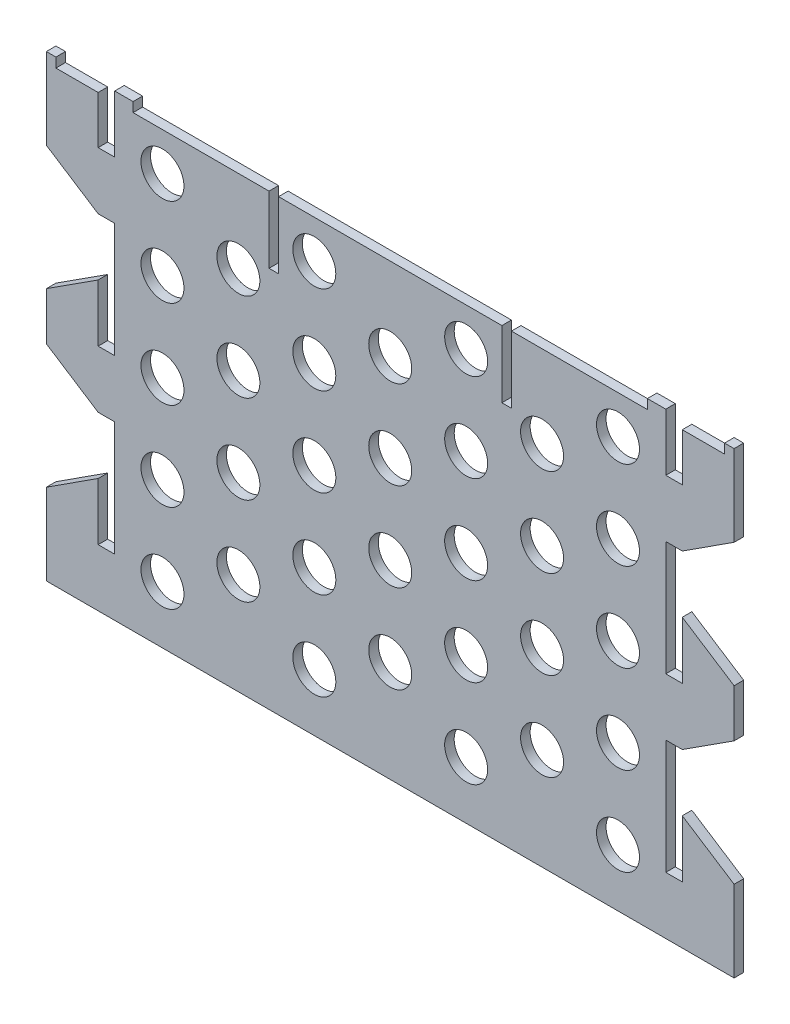
SolidWorks part; units mm, degrees
material "Plywood"
ref_plane "Front Plane" through (0, 0, 0) normal (0, 0, 1) x (1, 0, 0)
ref_plane "Top Plane" through (0, 0, 0) normal (0, 1, 0) x (1, 0, 0)
ref_plane "Right Plane" through (0, 0, 0) normal (1, 0, 0) x (0, 0, -1)
sketch "Sketch1" plane through (0, 0, 0) normal (0, 1, 0) x (1, 0, 0)
  line L0 (-381, -659.9114) -> (381, -659.9114) construction
  line L1 (-381, -659.9114) -> (381, -659.9114)
  line L2 (-381, -647.2114) -> (381, -647.2114)
  line L3 (-381, -647.2114) -> (-381, -659.9114)
  line L4 (381, -647.2114) -> (381, -659.9114)
  dimension "D1" = 12.7
extrude "Boss-Extrude1" add sketch "Sketch1" along normal blind 609.6
sketch "Sketch2" plane through (381, 0, 0) normal (1, 0, 0) x (0, 0, -1)
  line L4 (-659.9114, 0) -> (-647.2114, 0)
  line L5 (-647.2114, 0) -> (-647.2114, 609.6)
  line L6 (-647.2114, 609.6) -> (-659.9114, 609.6)
  line L7 (-659.9114, 609.6) -> (-659.9114, 0)
  line L8 (-659.9114, 0) -> (-647.2114, 0)
  line L9 (-647.2114, 0) -> (-647.2114, 609.6)
  line L10 (-647.2114, 609.6) -> (-659.9114, 609.6)
  line L11 (-659.9114, 609.6) -> (-659.9114, 0)
  dimension "D1" = 0
extrude "Boss-Extrude2" add sketch "Sketch2" along normal blind 76.2
mirror "Mirror1" about plane through (0, 0, 0) normal (1, 0, 0) of "Boss-Extrude2"
sketch "Sketch3" plane through (0, 0, 659.9114) normal (0, 0, 1) x (1, 0, 0)
  line L3 (-457.2, 0) -> (457.2, 0) construction
  line L5 (-457.2, 609.6) -> (457.2, 609.6) construction
  line L6 (-457.2, 76.2) -> (457.2, 76.2) construction
  line L8 (-388.3323, 0) -> (-388.3323, 609.6) construction
  line L9 (-366.3353, 0) -> (-366.3353, 609.6) construction
  line L10 (366.3353, 0) -> (366.3353, 609.6) construction
  line L11 (-457.2, 457.2) -> (457.2, 457.2) construction
  line L12 (-457.2, 533.4) -> (457.2, 533.4) construction
  line L26 (388.3323, 0) -> (388.3323, 609.6) construction
  line L44 (-457.2, 152.4) -> (457.2, 152.4) construction
  line L65 (-457.2, 0) -> (457.2, 0) construction
  line L67 (-457.2, 609.6) -> (457.2, 609.6) construction
  line L68 (-457.2, 76.2) -> (457.2, 76.2) construction
  line L69 (-457.2, 609.6) -> (457.2, 609.6) construction
  line L70 (-388.3323, 0) -> (-388.3323, 609.6) construction
  line L71 (-366.3353, 0) -> (-366.3353, 609.6) construction
  line L72 (366.3353, 0) -> (366.3353, 609.6) construction
  line L73 (388.3323, 0) -> (388.3323, 609.6) construction
  line L93 (-457.2, 152.4) -> (457.2, 152.4) construction
  line L94 (-457.2, 304.8) -> (457.2, 304.8) construction
  line L95 (-457.2, 609.6) -> (-457.2, 0) construction
  line L113 (457.2, 609.6) -> (457.2, 0) construction
  line L114 (-457.2, 228.6) -> (457.2, 228.6) construction
  line L115 (-457.2, 381) -> (457.2, 381) construction
  line L116 (0, 609.6) -> (0, 0) construction
  line L117 (366.3353, 609.6) -> (-366.3353, 609.6)
  line L118 (-366.3353, 609.6) -> (-366.3353, 533.4)
  line L119 (-366.3353, 533.4) -> (-388.3323, 533.4)
  line L120 (-388.3323, 533.4) -> (-388.3323, 609.6)
  line L121 (-388.3323, 609.6) -> (-457.2, 609.6)
  line L122 (-457.2, 609.6) -> (-457.2, 457.2)
  line L123 (-457.2, 457.2) -> (-366.3353, 457.2)
  line L124 (-366.3353, 457.2) -> (-366.3353, 304.8)
  line L125 (-366.3353, 304.8) -> (-388.3323, 304.8)
  line L126 (-388.3323, 304.8) -> (-388.3323, 381)
  line L127 (-388.3323, 381) -> (-457.2, 381)
  line L128 (-457.2, 381) -> (-457.2, 228.6)
  line L129 (-457.2, 228.6) -> (-366.3353, 228.6)
  line L130 (-366.3353, 228.6) -> (-366.3353, 76.2)
  line L131 (-366.3353, 76.2) -> (-388.3323, 76.2)
  line L132 (-388.3323, 76.2) -> (-388.3323, 152.4)
  line L133 (-388.3323, 152.4) -> (-457.2, 152.4)
  line L134 (-457.2, 152.4) -> (-457.2, 0)
  line L135 (-457.2, 0) -> (457.2, 0)
  line L136 (366.3353, 0) -> (366.3353, 609.6) construction
  line L137 (388.3323, 0) -> (388.3323, 609.6) construction
  line L138 (457.2, 152.4) -> (457.2, 0)
  line L139 (388.3323, 152.4) -> (457.2, 152.4)
  line L140 (388.3323, 76.2) -> (388.3323, 152.4)
  line L141 (366.3353, 76.2) -> (388.3323, 76.2)
  line L142 (366.3353, 228.6) -> (366.3353, 76.2)
  line L143 (457.2, 228.6) -> (366.3353, 228.6)
  line L144 (457.2, 381) -> (457.2, 228.6)
  line L145 (388.3323, 381) -> (457.2, 381)
  line L146 (388.3323, 304.8) -> (388.3323, 381)
  line L147 (366.3353, 304.8) -> (388.3323, 304.8)
  line L148 (366.3353, 457.2) -> (366.3353, 304.8)
  line L149 (457.2, 457.2) -> (366.3353, 457.2)
  line L150 (457.2, 609.6) -> (457.2, 457.2)
  line L151 (388.3323, 609.6) -> (457.2, 609.6)
  line L152 (388.3323, 533.4) -> (388.3323, 609.6)
  line L153 (366.3353, 533.4) -> (388.3323, 533.4)
  line L154 (366.3353, 609.6) -> (366.3353, 533.4)
  point P0 (-457.2, 457.2)
  point P61 (-366.3353, 548.966)
  point P63 (-366.3353, 484.904)
  point P64 (0, 0)
  point P65 (0, 0)
  dimension "D1" = 76.2
  dimension "D2" = 76.2
  dimension "D3" = 76.2
  dimension "D4" = 76.2
extrude "Cut-Extrude1" cut sketch "Sketch3" against normal up to vertex (12.7 mm away) flip side to cut
sketch "Sketch4" plane through (0, 0, 659.9114) normal (0, 0, 1) x (1, 0, 0)
  line L0 (0, 0) -> (0, 609.6)
  line L1 (-366.3353, 609.6) -> (366.3353, 609.6) construction
sketch "Sketch6" plane through (0, 609.6, 0) normal (0, 1, 0) x (1, 0, 0)
  line L20 (-444.5, -647.2114) -> (-444.5, -659.9114)
  line L21 (-444.5, -659.9114) -> (-388.3323, -659.9114)
  line L22 (-388.3323, -659.9114) -> (-388.3323, -647.2114)
  line L23 (-388.3323, -647.2114) -> (-444.5, -647.2114)
  line L24 (-444.5, -647.2114) -> (-444.5, -659.9114)
  line L25 (-444.5, -659.9114) -> (-388.3323, -659.9114)
  line L26 (-388.3323, -659.9114) -> (-388.3323, -647.2114)
  line L27 (-388.3323, -647.2114) -> (-444.5, -647.2114)
  line L28 (341.9177, -659.9114) -> (341.9177, -647.2114)
  line L29 (-341.9177, -659.9114) -> (341.9177, -659.9114)
  line L30 (-341.9177, -647.2114) -> (-341.9177, -659.9114)
  line L31 (341.9177, -647.2114) -> (-341.9177, -647.2114)
  line L32 (341.9177, -659.9114) -> (341.9177, -647.2114)
  line L33 (-341.9177, -659.9114) -> (341.9177, -659.9114)
  line L34 (-341.9177, -647.2114) -> (-341.9177, -659.9114)
  line L35 (341.9177, -647.2114) -> (-341.9177, -647.2114)
  line L36 (388.3323, -647.2114) -> (388.3323, -659.9114)
  line L37 (444.5, -647.2114) -> (388.3323, -647.2114)
  line L38 (444.5, -659.9114) -> (444.5, -647.2114)
  line L39 (388.3323, -659.9114) -> (444.5, -659.9114)
  line L48 (388.3323, -647.2114) -> (388.3323, -659.9114)
  line L49 (444.5, -647.2114) -> (388.3323, -647.2114)
  line L50 (444.5, -659.9114) -> (444.5, -647.2114)
  line L51 (388.3323, -659.9114) -> (444.5, -659.9114)
  dimension "D1" = 0
  dimension "D2" = 0
  dimension "D3" = 0
extrude "Cut-Extrude2" cut sketch "Sketch6" against normal up to vertex (12.7 mm away)
sketch "Sketch14" plane through (0, 0, 659.9114) normal (0, 0, 1) x (1, 0, 0)
  line L0 (-388.3323, 457.2) -> (-457.2, 501.65)
  line L1 (-457.2, 609.6) -> (-457.2, 457.2) construction
  line L3 (-457.2, 457.2) -> (-388.3323, 457.2)
  line L4 (0, 0) -> (0, 596.9) construction
  line L5 (-457.2, 0) -> (457.2, 0) construction
  line L6 (-341.9177, 596.9) -> (341.9177, 596.9) construction
  line L7 (-388.3323, 381) -> (-457.2, 336.55)
  line L8 (-457.2, 381) -> (-457.2, 228.6) construction
  line L12 (-457.2, 336.55) -> (-457.2, 381)
  line L13 (-457.2, 381) -> (-388.3323, 381)
  line L14 (-388.3323, 152.4) -> (-457.2, 107.95)
  line L15 (-457.2, 152.4) -> (-457.2, 0) construction
  line L16 (-457.2, 107.95) -> (-457.2, 152.4)
  line L17 (-457.2, 152.4) -> (-388.3323, 152.4)
  line L18 (457.2, 152.4) -> (388.3323, 152.4)
  line L19 (457.2, 107.95) -> (457.2, 152.4)
  line L20 (388.3323, 152.4) -> (457.2, 107.95)
  line L21 (457.2, 381) -> (388.3323, 381)
  line L22 (457.2, 336.55) -> (457.2, 381)
  line L23 (388.3323, 381) -> (457.2, 336.55)
  line L24 (457.2, 457.2) -> (388.3323, 457.2)
  line L25 (457.2, 501.65) -> (457.2, 457.2)
  line L26 (388.3323, 457.2) -> (457.2, 501.65)
  line L33 (-457.2, 273.05) -> (-388.3323, 228.6)
  line L34 (-457.2, 228.6) -> (-366.3353, 228.6) construction
  line L35 (-388.3323, 228.6) -> (-457.2, 228.6)
  line L36 (-457.2, 228.6) -> (-457.2, 273.05)
  line L37 (-457.2, 501.65) -> (-457.2, 457.2)
  line L38 (388.3323, 228.6) -> (457.2, 228.6)
  line L39 (457.2, 273.05) -> (388.3323, 228.6)
  line L40 (457.2, 228.6) -> (457.2, 273.05)
  line L41 (-457.2, 457.2) -> (-366.3353, 457.2) construction
  dimension "D1" = 44.45
extrude "Cut-Extrude5" cut sketch "Sketch14" against normal up to vertex (12.7 mm away)
ref_plane "Plane1" through (0, 304.8, 0) normal (0, -1, 0) x (-1, 0, 0)
sketch "Sketch7" plane through (0, 0, 659.9114) normal (0, 0, 1) x (1, 0, 0)
  line L1171 (148.4706, 508) -> (161.1706, 508)
  line L1172 (161.1706, 508) -> (161.1706, 596.9)
  line L1173 (161.1706, 596.9) -> (148.4706, 596.9)
  line L1174 (148.4706, 596.9) -> (148.4706, 508)
  line L1175 (148.4706, 508) -> (161.1706, 508)
  line L1176 (161.1706, 508) -> (161.1706, 596.9)
  line L1177 (161.1706, 596.9) -> (148.4706, 596.9)
  line L1178 (148.4706, 596.9) -> (148.4706, 508)
  line L1179 (-148.4706, 596.9) -> (-161.1706, 596.9)
  line L1180 (-148.4706, 508) -> (-148.4706, 596.9)
  line L1181 (-161.1706, 508) -> (-148.4706, 508)
  line L1182 (-161.1706, 596.9) -> (-161.1706, 508)
  line L1183 (-148.4706, 596.9) -> (-161.1706, 596.9)
  line L1184 (-148.4706, 508) -> (-148.4706, 596.9)
  line L1185 (-161.1706, 508) -> (-148.4706, 508)
  line L1186 (-161.1706, 596.9) -> (-161.1706, 508)
  dimension "D1" = 0
  dimension "D2" = 0
extrude "Cut-Extrude3" cut sketch "Sketch7" against normal up to vertex (12.7 mm away)
mirror "Mirror2" about plane through (0, 304.8, 0) normal (0, -1, 0) of "Cut-Extrude3", "Cut-Extrude2"
sketch "Sketch8" [suppressed] plane through (0, 609.6, 0) normal (0, 1, 0) x (1, 0, 0)
  line L16 (366.3353, -647.2114) -> (366.3353, -659.9114) construction
  line L17 (-366.3353, -647.2114) -> (-366.3353, -659.9114) construction
  line L18 (366.3353, -647.2114) -> (366.3353, -659.9114)
  line L19 (-366.3353, -647.2114) -> (-366.3353, -659.9114)
  line L20 (-366.3353, -647.2114) -> (366.3353, -647.2114)
  line L21 (366.3353, -659.9114) -> (-366.3353, -659.9114)
extrude "Boss-Extrude3" [suppressed] add sketch "Sketch8" against normal up to vertex
sketch "Sketch9" [suppressed] plane through (0, 609.6, 0) normal (0, 1, 0) x (1, 0, 0)
  line L0 (388.3323, -647.2114) -> (388.3323, -659.9114) construction
  line L1 (457.2, -647.2114) -> (457.2, -659.9114) construction
  line L2 (-457.2, -647.2114) -> (-457.2, -659.9114) construction
  line L3 (-388.3323, -659.9114) -> (-388.3323, -647.2114) construction
  line L4 (388.3323, -647.2114) -> (388.3323, -659.9114)
  line L5 (457.2, -647.2114) -> (457.2, -659.9114)
  line L6 (-457.2, -647.2114) -> (-457.2, -659.9114)
  line L7 (-388.3323, -659.9114) -> (-388.3323, -647.2114)
  line L8 (-457.2, -659.9114) -> (-388.3323, -659.9114)
  line L9 (-388.3323, -647.2114) -> (-457.2, -647.2114)
  line L10 (388.3323, -659.9114) -> (457.2, -659.9114)
  line L11 (457.2, -647.2114) -> (388.3323, -647.2114)
extrude "Boss-Extrude4" [suppressed] add sketch "Sketch9" against normal up to vertex
sketch "Sketch10" plane through (0, 0, 659.9114) normal (0, 0, 1) x (1, 0, 0)
  line L0 (-148.4706, 12.7) -> (148.4706, 12.7) construction
  line L1 (-366.3353, 609.6) -> (366.3353, 609.6) construction
  line L2 (-366.3353, 609.6) -> (-366.3353, 12.7) construction
  line L3 (-366.3353, 12.7) -> (366.3353, 12.7) construction
  line L4 (366.3353, 609.6) -> (366.3353, 12.7) construction
  line L5 (-366.3353, 311.15) -> (366.3353, 311.15) construction
  line L6 (0, 252.4125) -> (0, 134.9375) construction
  line L7 (-302.8353, 311.15) -> (-302.8353, 193.675) construction
  line L8 (-302.8353, 193.675) -> (-302.8353, 76.2) construction
  line L9 (-366.3353, 193.675) -> (-302.8353, 193.675) construction
  line L10 (-302.8353, 193.675) -> (-100.9451, 193.675) construction
  line L11 (-100.9451, 193.675) -> (100.9451, 193.675) construction
  line L12 (100.9451, 193.675) -> (302.8353, 193.675) construction
  line L13 (302.8353, 193.675) -> (366.3353, 193.675) construction
  line L14 (366.3353, 76.2) -> (366.3353, 228.6) construction
  line L15 (-302.8353, 76.2) -> (-302.8353, 12.7) construction
  line L16 (-201.8902, 252.4125) -> (-201.8902, 134.9375) construction
  line L17 (-201.8902, 252.4125) -> (-201.8902, 369.8875) construction
  line L18 (201.8902, 252.4125) -> (201.8902, 134.9375) construction
  circle A0 centre (-302.8353, 311.15) radius 28.575
  circle A1 centre (-302.8353, 193.675) radius 28.575
  circle A2 centre (-302.8353, 76.2) radius 28.575
  circle A3 centre (-100.9451, 76.2) radius 28.575
  circle A4 centre (-100.9451, 193.675) radius 28.575
  circle A5 centre (-100.9451, 311.15) radius 28.575
  circle A6 centre (-201.8902, 252.4125) radius 28.575
  circle A7 centre (-201.8902, 134.9375) radius 28.575
  circle A8 centre (100.9451, 193.675) radius 28.575
  circle A9 centre (302.8353, 193.675) radius 28.575
  circle A10 centre (100.9451, 311.15) radius 28.575
  circle A11 centre (302.8353, 311.15) radius 28.575
  circle A12 centre (100.9451, 76.2) radius 28.575
  circle A13 centre (302.8353, 76.2) radius 28.575
  circle A14 centre (0, 134.9375) radius 28.575
  circle A15 centre (0, 252.4125) radius 28.575
  circle A16 centre (201.8902, 252.4125) radius 28.575
  circle A17 centre (201.8902, 134.9375) radius 28.575
  circle A18 centre (302.8353, 546.1) radius 28.575
  circle A19 centre (302.8353, 428.625) radius 28.575
  circle A20 centre (201.8902, 369.8875) radius 28.575
  circle A21 centre (201.8902, 487.3625) radius 28.575
  circle A22 centre (100.9451, 546.1) radius 28.575
  circle A23 centre (100.9451, 428.625) radius 28.575
  circle A24 centre (0, 487.3625) radius 28.575
  circle A25 centre (0, 369.8875) radius 28.575
  circle A26 centre (-100.9451, 428.625) radius 28.575
  circle A27 centre (-100.9451, 546.1) radius 28.575
  circle A28 centre (-201.8902, 487.3625) radius 28.575
  circle A29 centre (-302.8353, 546.1) radius 28.575
  circle A30 centre (-302.8353, 428.625) radius 28.575
  circle A31 centre (-201.8902, 369.8875) radius 28.575
  point P8 (0, 12.7)
  point P20 (-201.8902, 193.675)
  point P30 (-201.8902, 193.675)
  point P31 (-201.8902, 311.15)
  point P41 (0, 193.675)
  point P57 (201.8902, 193.675)
  dimension "D2" = 57.15
  dimension "D1" = 63.5
extrude "Cut-Extrude4" cut sketch "Sketch10" against normal through all
sketch "Sketch11" plane through (0, 12.7, 0) normal (0, -1, 0) x (1, 0, 0)
  line L0 (161.1706, 659.9114) -> (148.4706, 659.9114) construction
  line L1 (148.4706, 659.9114) -> (148.4706, 647.2114) construction
  line L2 (148.4706, 647.2114) -> (161.1706, 647.2114) construction
  line L3 (161.1706, 647.2114) -> (161.1706, 659.9114) construction
  line L4 (-148.4706, 659.9114) -> (-161.1706, 659.9114) construction
  line L5 (-161.1706, 659.9114) -> (-161.1706, 647.2114) construction
  line L6 (-161.1706, 647.2114) -> (-148.4706, 647.2114) construction
  line L7 (-148.4706, 647.2114) -> (-148.4706, 659.9114) construction
  line L8 (161.1706, 659.9114) -> (148.4706, 659.9114)
  line L9 (148.4706, 659.9114) -> (148.4706, 647.2114)
  line L10 (148.4706, 647.2114) -> (161.1706, 647.2114)
  line L11 (161.1706, 647.2114) -> (161.1706, 659.9114)
  line L12 (-148.4706, 659.9114) -> (-161.1706, 659.9114)
  line L13 (-161.1706, 659.9114) -> (-161.1706, 647.2114)
  line L14 (-161.1706, 647.2114) -> (-148.4706, 647.2114)
  line L15 (-148.4706, 647.2114) -> (-148.4706, 659.9114)
extrude "Boss-Extrude5" add sketch "Sketch11" against normal up to vertex
sketch "Sketch12" plane through (0, 12.7, 0) normal (0, -1, 0) x (1, 0, 0)
  line L0 (444.5, 659.9114) -> (388.3323, 659.9114) construction
  line L1 (388.3323, 659.9114) -> (388.3323, 647.2114) construction
  line L2 (388.3323, 647.2114) -> (444.5, 647.2114) construction
  line L3 (444.5, 647.2114) -> (444.5, 659.9114) construction
  line L4 (-444.5, 647.2114) -> (-388.3323, 647.2114) construction
  line L5 (-388.3323, 647.2114) -> (-388.3323, 659.9114) construction
  line L6 (-388.3323, 659.9114) -> (-444.5, 659.9114) construction
  line L7 (-444.5, 659.9114) -> (-444.5, 647.2114) construction
  line L8 (-341.9177, 659.9114) -> (-341.9177, 647.2114) construction
  line L9 (-341.9177, 647.2114) -> (341.9177, 647.2114) construction
  line L10 (341.9177, 647.2114) -> (341.9177, 659.9114) construction
  line L11 (341.9177, 659.9114) -> (-341.9177, 659.9114) construction
  line L12 (444.5, 659.9114) -> (388.3323, 659.9114)
  line L13 (388.3323, 659.9114) -> (388.3323, 647.2114)
  line L14 (388.3323, 647.2114) -> (444.5, 647.2114)
  line L15 (444.5, 647.2114) -> (444.5, 659.9114)
  line L16 (-444.5, 647.2114) -> (-388.3323, 647.2114)
  line L17 (-388.3323, 647.2114) -> (-388.3323, 659.9114)
  line L18 (-388.3323, 659.9114) -> (-444.5, 659.9114)
  line L19 (-444.5, 659.9114) -> (-444.5, 647.2114)
  line L20 (-341.9177, 659.9114) -> (-341.9177, 647.2114)
  line L21 (-341.9177, 647.2114) -> (341.9177, 647.2114)
  line L22 (341.9177, 647.2114) -> (341.9177, 659.9114)
  line L23 (341.9177, 659.9114) -> (-341.9177, 659.9114)
extrude "Boss-Extrude6" add sketch "Sketch12" along normal up to vertex (12.7 mm away)
